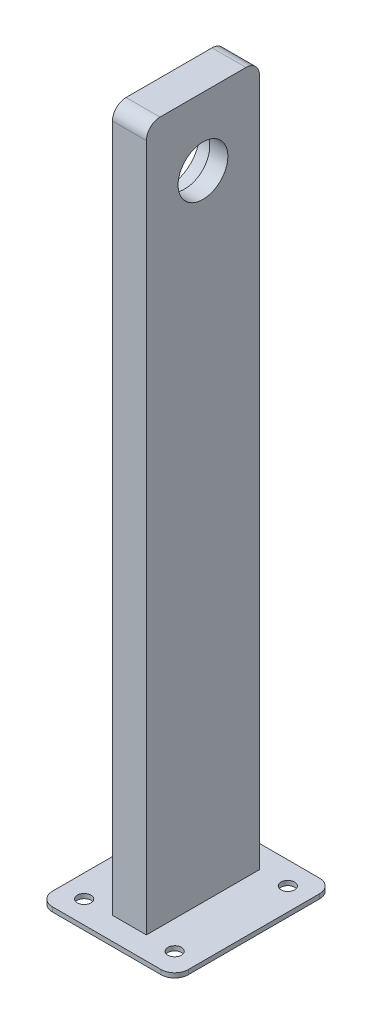
SolidWorks part; units mm, degrees
ref_plane "Front Plane" through (0, 0, 0) normal (0, 0, 1) x (1, 0, 0)
ref_plane "Top Plane" through (0, 0, 0) normal (0, 1, 0) x (1, 0, 0)
ref_plane "Right Plane" through (0, 0, 0) normal (1, 0, 0) x (0, 0, -1)
sketch "Sketch1" plane through (0, 0, 0) normal (0, 1, 0) x (1, 0, 0)
  line L1 (-7.5, 25) -> (7.5, 25)
  line L2 (-7.5, 25) -> (-7.5, -25)
  line L3 (-7.5, -25) -> (7.5, -25)
  line L4 (7.5, 25) -> (7.5, -25)
  line L5 (-7.5, 25) -> (7.5, -25) construction
  line L6 (-7.5, -25) -> (7.5, 25) construction
  point P0 (0, 0)
  dimension "D1" = 50
  dimension "D2" = 15
extrude "Boss-Extrude1" add sketch "Sketch1" along normal blind 310
sketch "Sketch2" plane through (0, 0, 0) normal (0, -1, 0) x (-1, 0, 0)
  line L1 (-30, -35) -> (30, -35)
  line L2 (-30, -35) -> (-30, 35)
  line L3 (-30, 35) -> (30, 35)
  line L4 (30, -35) -> (30, 35)
  line L5 (-30, -35) -> (30, 35) construction
  line L6 (-30, 35) -> (30, -35) construction
  point P0 (0, 0)
  dimension "D1" = 60
  dimension "D2" = 70
extrude "Boss-Extrude2" add sketch "Sketch2" along normal blind 2
sketch "Sketch4" plane through (0, 0, 0) normal (0, 1, 0) x (1, 0, 0)
  line L0 (30, 35) -> (30, -35) construction
  line L1 (30, -35) -> (-30, -35) construction
  line L2 (0, 0) -> (18.9049, 0) construction
  line L3 (0, 0) -> (0, -13.6613) construction
  circle A0 centre (20, -25) radius 3
  circle A1 centre (-20, -25) radius 3
  circle A2 centre (-20, 25) radius 3
  circle A3 centre (20, 25) radius 3
  dimension "D1" = 10
  dimension "D3" = 6
  dimension "D2" = 10
extrude "Cut-Extrude1" cut sketch "Sketch4" against normal blind 2
fillet "Fillet1" radius 6 4 edges at (30, -1, -35) (30, -1, 35) (-30, -1, -35) (-30, -1, 35)
sketch "Sketch5" plane through (-7.5, 0, 0) normal (-1, 0, 0) x (0, 0, 1)
  line L0 (-25, 310) -> (25, 310) construction
  circle A0 centre (0, 280) radius 13.5
  dimension "D1" = 30
  dimension "D2" = 27
extrude "Cut-Extrude2" cut sketch "Sketch5" against normal blind 7
sketch "Sketch6" plane through (-0.5, 0, 0) normal (-1, 0, 0) x (0, 0, 1)
  circle A0 centre (0, 280) radius 11
extrude "Cut-Extrude3" cut sketch "Sketch6" against normal through all
fillet "Fillet2" radius 6 2 edges at (0, 310, -25) (0, 310, 25)
